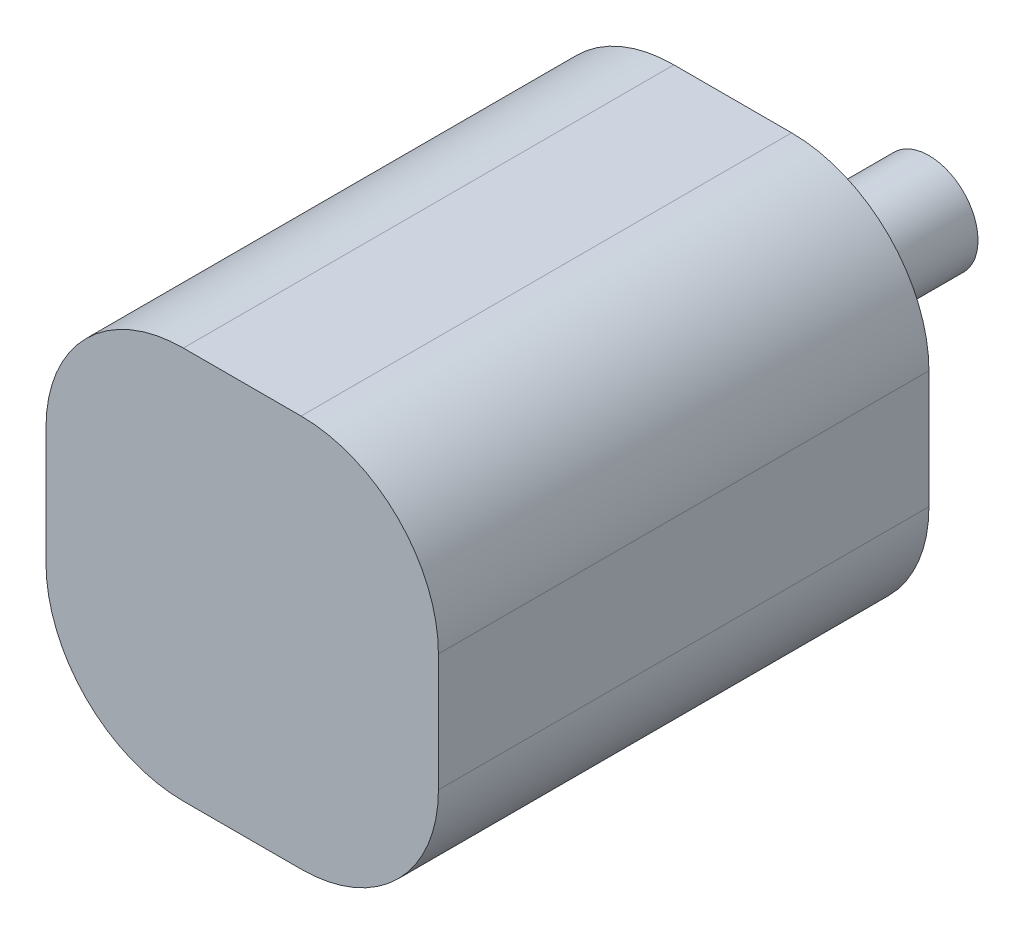
SolidWorks part; units mm, degrees
ref_plane "Front Plane" through (0, 0, 0) normal (0, 0, 1) x (1, 0, 0)
ref_plane "Top Plane" through (0, 0, 0) normal (0, 1, 0) x (1, 0, 0)
ref_plane "Right Plane" through (0, 0, 0) normal (1, 0, 0) x (0, 0, -1)
sketch "Sketch1" plane through (0, 0, 0) normal (0, 0, 1) x (1, 0, 0)
  circle A0 centre (0, 0) radius 2.5
extrude "Boss-Extrude1" add sketch "Sketch1" along normal blind 10
sketch "Sketch2" plane through (0, 0, 10) normal (0, 0, 1) x (1, 0, 0)
  line L1 (-10, 10) -> (10, 10)
  line L2 (-10, 10) -> (-10, -10)
  line L3 (-10, -10) -> (10, -10)
  line L4 (10, 10) -> (10, -10)
  line L5 (-10, 10) -> (10, -10) construction
  line L6 (-10, -10) -> (10, 10) construction
  point P0 (0, 0)
  dimension "D1" = 20
  dimension "D2" = 20
extrude "Boss-Extrude2" add sketch "Sketch2" along normal blind 25
fillet "Fillet1" radius 7 4 edges at (-10, -10, 22.5) (-10, 10, 22.5) (10, -10, 22.5) (10, 10, 22.5)
